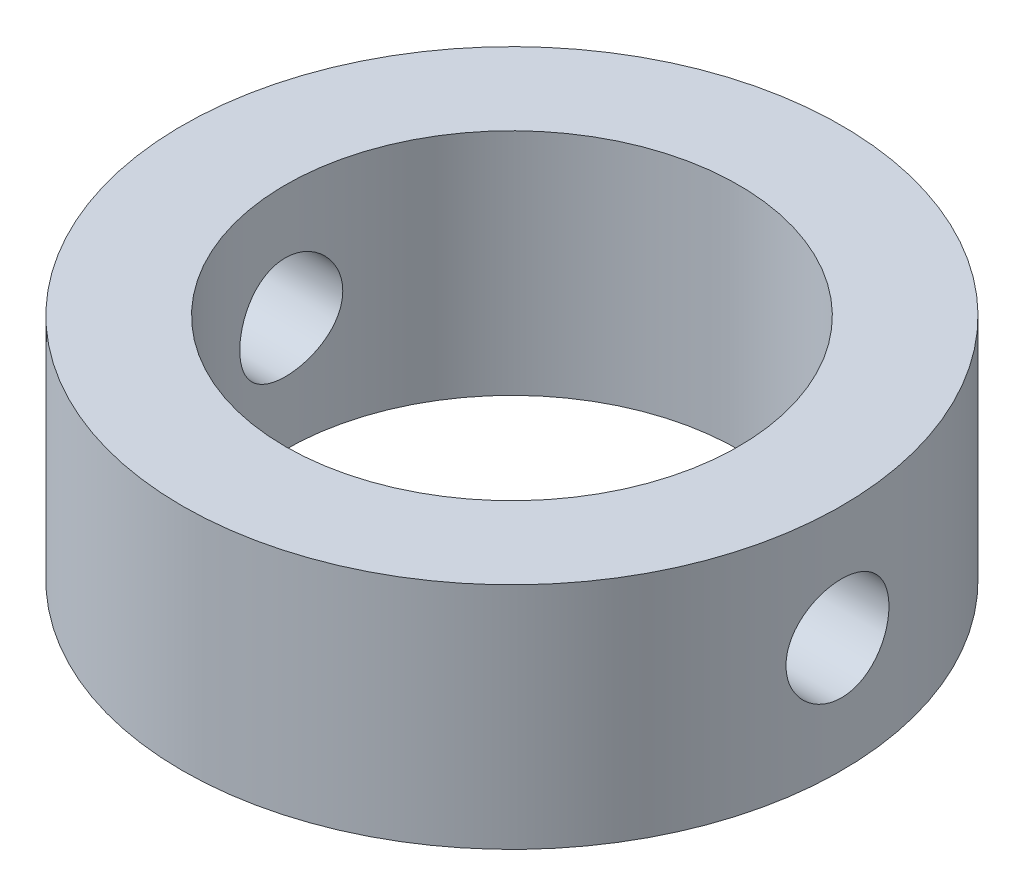
SolidWorks part; units mm, degrees
ref_plane "Front Plane" through (0, 0, 0) normal (0, 0, 1) x (1, 0, 0)
ref_plane "Top Plane" through (0, 0, 0) normal (0, 1, 0) x (1, 0, 0)
ref_plane "Right Plane" through (0, 0, 0) normal (1, 0, 0) x (0, 0, -1)
sketch "Sketch1" plane through (0, 0, 0) normal (0, 0, 1) x (1, 0, 0)
  line L0 (0, 18.455) -> (0, -21.2807) construction
  line L2 (-16, 5.563) -> (-11, 5.563)
  line L3 (-16, 5.563) -> (-16, -5.563)
  line L4 (-16, -5.563) -> (-11, -5.563)
  line L5 (-11, 5.563) -> (-11, -5.563)
  line L6 (-16, 5.563) -> (-11, -5.563) construction
  line L7 (-16, -5.563) -> (-11, 5.563) construction
  point P3 (-13.5, 0)
  dimension "D1" = 16
  dimension "D2" = 11
revolve "Revolve1" add sketch "Sketch1" angle 360 about L0
sketch "Sketch2" plane through (0, 0, 0) normal (1, 0, 0) x (0, 0, -1)
  circle A0 centre (0, 0) radius 2.5
  dimension "D1" = 5
extrude "Cut-Extrude1" cut sketch "Sketch2" against normal through all both and the other way through all
